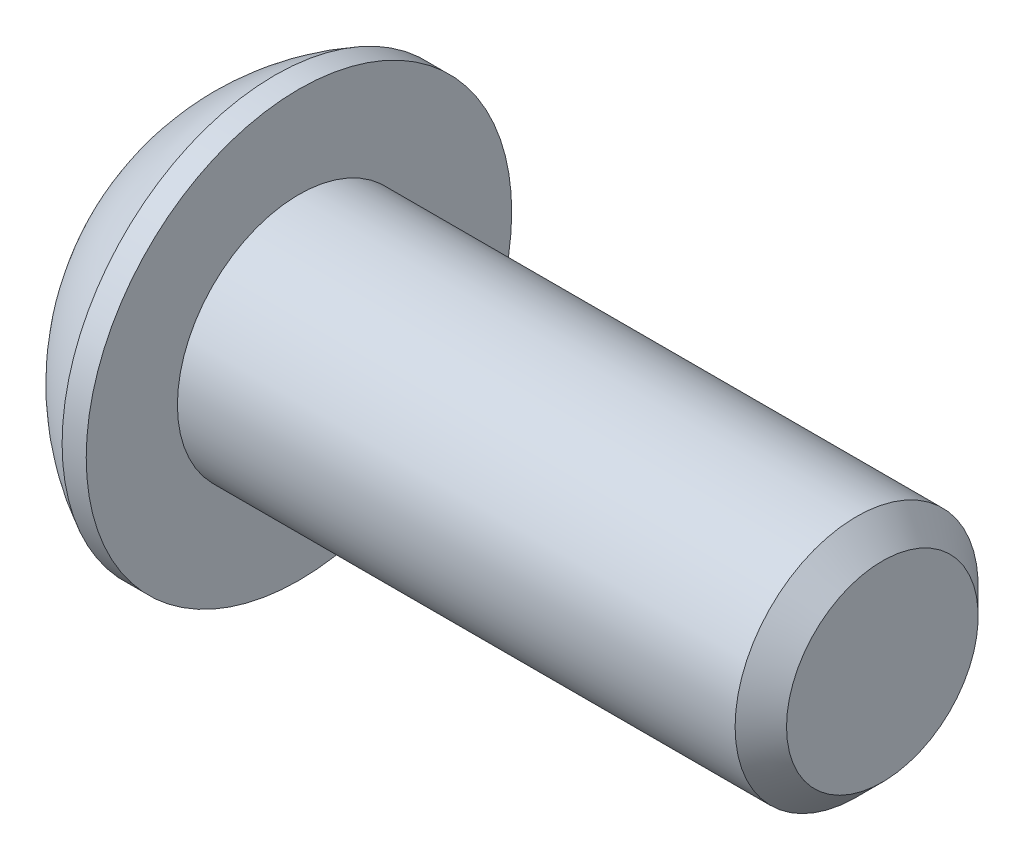
SolidWorks part; units mm, degrees
ref_plane "Plane1"
ref_plane "Plane2" through (0, 0, 0) normal (0, 1, 0) x (1, 0, 0)
ref_plane "Plane3" through (0, 0, 0) normal (1, 0, 0) x (0, 0, -1)
sketch "BodySke" plane through (0, 0, 0) normal (0, 0, 1) x (1, 0, 0)
  line L0 (23.2664, 0) -> (23.2664, 3.1293)
  line L1 (22.4269, 3.9687) -> (4.2164, 3.9687)
  line L2 (4.2164, 3.9687) -> (4.2164, 6.9469)
  line L3 (4.2164, 6.9469) -> (3.429, 6.9469)
  line L4 (0, 0) -> (101.6, 0) construction
  line L5 (4.2164, -6.9469) -> (3.429, -6.9469) construction
  line L6 (55.6768, -3.9688) -> (4.2164, -3.9687) construction
  line L7 (23.2664, 0) -> (0, 0)
  line L8 (0, 3.4735) -> (0, -3.4735) construction
  line L9 (0, 0) -> (0, 3.4735)
  line L10 (23.2664, 3.1293) -> (22.4269, 3.9687)
  line L11 (23.2664, -3.1293) -> (22.4269, -3.9687) construction
  line L12 (5.6261, 9.525) -> (5.6261, -3.9687) construction
  line L13 (4.2164, 9.525) -> (4.2164, -3.9687) construction
  arc A1 (0, 3.4735) -> (3.429, 6.9469) centre (6.9922, 0) cw
  dimension "D1" = 6.9469
  dimension "Diameter" = 7.9375
  dimension "Length" = 19.05
  dimension "Head_dia" = 13.8938
  dimension "Head_ht" = 4.2164
  dimension "Head_side_ht" = 0.7874
  dimension "Minor_dia" = 6.2586
  dimension "Body_ch_ang" = 45
  dimension "Advance" = 1.4097
  dimension "Thread_nom" = 19.05
revolve "BaseBody" add sketch "BodySke" angle 360 about L4
cosmetic thread "ThreadCosmetic" parameters "Thread_length"=17.6403, "Thread_minor"=6.2586
sketch "Sketch2" plane through (0, 0, 0) normal (0, 0, 1) x (1, 0, 0)
  line L0 (0, 2.3876) -> (2.667, 2.3876)
  line L1 (2.667, 2.3876) -> (4.0455, 0)
  line L3 (4.0455, 0) -> (0, 0)
  line L4 (0, 0) -> (0, 2.3876)
  line L5 (0, -2.3876) -> (2.667, -2.3876) construction
  line L6 (0, 0) -> (47.625, 0) construction
  dimension "D2" = 60
  dimension "PreBroach_depth" = 2.667
  dimension "PreBroach_dia" = 4.7752
revolve "PreBroach" cut sketch "Sketch2" angle 360 about L6
sketch "Sketch3" plane through (0, 0, 0) normal (1, 0, 0) x (0, 0, -1)
  line L0 (-2.3876, -1.3785) -> (-2.3876, 1.3785)
  line L1 (-2.3876, 1.3785) -> (0, 2.757)
  line L2 (0, 2.757) -> (2.3876, 1.3785)
  line L3 (2.3876, 1.3785) -> (2.3876, -1.3785)
  line L4 (2.3876, -1.3785) -> (0, -2.757)
  line L5 (0, -2.757) -> (-2.3876, -1.3785)
  dimension "D1" = 2.3876
  dimension "D2" = 2.3876
  dimension "D3" = 4.7752
  dimension "Hex_size" = 4.7752
extrude "Hex" cut sketch "Sketch3" along normal blind 2.667
sketch "Sketch4" plane through (0, 9.525, 0) normal (1, 0, 0) x (0, 0, -1)
  line L0 (0, -9.525) -> (2.8067, -9.525)
  line L1 (0, -9.525) -> (6.1484, -5.9752) construction
  line L2 (0, -9.525) -> (1.4033, -7.0943)
  line L3 (2.3336, -8.911) -> (2.6851, -8.708)
  line L4 (1.6986, -7.8111) -> (2.0501, -7.6081)
  arc A0 (2.3336, -8.911) -> (1.6986, -7.8111) centre (0, -9.525) ccw
  arc A1 (2.8067, -9.525) -> (2.6851, -8.708) centre (0, -9.525) ccw
  arc A2 (1.4033, -7.0943) -> (2.0501, -7.6081) centre (0, -9.525) cw
  dimension "D1" = 30
  dimension "Spline_n_dim" = 4.826
  dimension "Spline_m_dim" = 5.6134
  dimension "D2" = 60
  dimension "D3" = 0.635
  dimension "Spline_p_dim" = 1.27
extrude "Spline" [suppressed] cut sketch "Sketch4" along normal blind 2.667
pattern_circular "CirPattern1" [suppressed] count 6 every 60 about axis through (0, 0, 0) along (1, 0, 0)
sketch "ThdSchSke" plane through (0, 0, 0) normal (0, 0, 1) x (1, 0, 0)
  line L0 (5.6261, -3.1293) -> (5.0383, -3.9688)
  line L1 (5.6261, -3.1293) -> (6.2139, -3.9688)
  line L2 (6.2139, -3.9688) -> (6.2139, -4.9609)
  line L3 (-3.175, 0) -> (5.1513, 0) construction
  line L4 (0, 1.3785) -> (0, 2.757) construction
  line L5 (6.2139, -4.9609) -> (5.0383, -4.9609)
  line L6 (5.0383, -4.9609) -> (5.0383, -3.9688)
  dimension "Thread_minor" = 6.2586
  dimension "Diameter" = 7.9375
  dimension "Start" = 5.6261
  dimension "SideAngle" = 55
  dimension "VeeAngle" = 70
  dimension "Overcut" = 9.9219
revolve "ThreadSchematic" [suppressed] cut sketch "ThdSchSke" angle 360 about L3
pattern_linear "ThdSchPat" [suppressed]
equation "\"D1@BodySke\" = \"Head_dia@BodySke\" * .5"
equation "\"Thread_minor@ThreadCosmetic\" = \"Minor_dia@BodySke\""
equation "\"D1@Sketch3\" = \"Hex_size@Sketch3\" / 2"
equation "\"D2@Sketch3\" = \"D1@Sketch3\""
equation "\"D3@Sketch3\" = \"Hex_size@Sketch3\""
equation "\"D3@Sketch4\" = \"Spline_p_dim@Sketch4\" / 2"
equation "\"D1@Sketch4\" = \"D2@Sketch4\" / 2"
equation "\"Thread_length@ThreadCosmetic\" = ((sgn( (\"Length@BodySke\" - \"Advance@BodySke\" ) - \"Thread_nom@BodySke\" )-1)*( (\"Length@BodySke\" - \"Advance@BodySke\" ) - \"Thread_nom@BodySke\" ))/-2+ \"Thread_nom@BodySke\""
equation "\"Thread_minor@ThdSchSke\" = \"Minor_dia@BodySke\""
equation "\"Diameter@ThdSchSke\" = \"Diameter@BodySke\""
equation "\"Overcut@ThdSchSke\" = \"Diameter@BodySke\" * 1.25"
equation "\"Start@ThdSchSke\" = \"Head_ht@BodySke\" + \"Length@BodySke\" - \"Thread_length@ThreadCosmetic\"  '---Non-countersunk---"
equation "\"Num_threads@ThdSchPat\" = int( \"Thread_length@ThreadCosmetic\" / \"Advance@BodySke\" + 0.999 )  + 1"
equation "\"Advance@ThdSchPat\" = \"Thread_length@ThreadCosmetic\" /  (\"Num_threads@ThdSchPat\" - 1) 'relax it"
equation "\"Num_threads@ThdSchPat\" = \"Num_threads@ThdSchPat\" - sgn( \"Num_threads@ThdSchPat\" - 1) '---chamfered tips only---"
